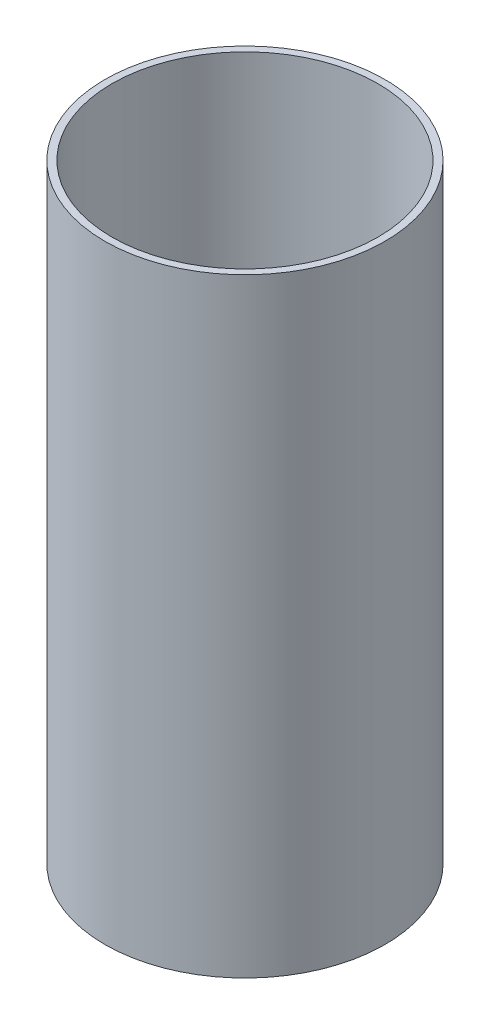
SolidWorks part; units mm, degrees
material "PVC Rigid"
ref_plane "Front Plane" through (0, 0, 0) normal (0, 0, 1) x (1, 0, 0)
ref_plane "Top Plane" through (0, 0, 0) normal (0, 1, 0) x (1, 0, 0)
ref_plane "Right Plane" through (0, 0, 0) normal (1, 0, 0) x (0, 0, -1)
sketch "Sketch1" plane through (0, 0, 0) normal (0, 1, 0) x (1, 0, 0)
  circle A0 centre (0, 0) radius 93.6625
  circle A1 centre (0, 0) radius 88.9
  dimension "D1" = 187.325
  dimension "D2" = 177.8
extrude "Boss-Extrude1" add sketch "Sketch1" along normal mid plane 407.162
ref_plane "Plane1" through (0, 0, 93.6625) normal (0, 0, 1) x (1, 0, 0)
sketch "Sketch3" plane through (0, 0, 93.6625) normal (0, 0, 1) x (1, 0, 0)
  line L0 (0, -55) -> (0, 55) construction
  line L1 (-93.6625, -203.581) -> (93.6625, -203.581) construction
  circle A0 centre (0, -197.231) radius 1.4351
  dimension "D1" = 2.8702
  dimension "D2" = 6.35
extrude "Cut-Extrude1" [suppressed] cut sketch "Sketch3" against normal blind 19.304
pattern_circular "CirPattern1" [suppressed] count 12 over 360
mirror "Mirror1" [suppressed] about plane through (0, 0, 0) normal (0, 1, 0)
sketch "Sketch4" [suppressed] plane through (0, 0, 93.6625) normal (0, 0, 1) x (1, 0, 0)
  line L0 (0, -103.0288) -> (0, 103.0288) construction
  circle A0 centre (0, 65.7606) radius 1.4351
  circle A1 centre (0, -65.7606) radius 1.4351
  circle A2 centre (0, 197.231) radius 1.4351 construction
  circle A3 centre (0, -197.231) radius 1.4351 construction
  dimension "D1" = 131.4704
  dimension "D2" = 131.4704
  dimension "D3" = 2.8702
  dimension "D4" = 2.8702
extrude "Cut-Extrude2" [suppressed] cut sketch "Sketch4" against normal blind 43.18
pattern_circular "CirPattern2" [suppressed] count 3 over 360
